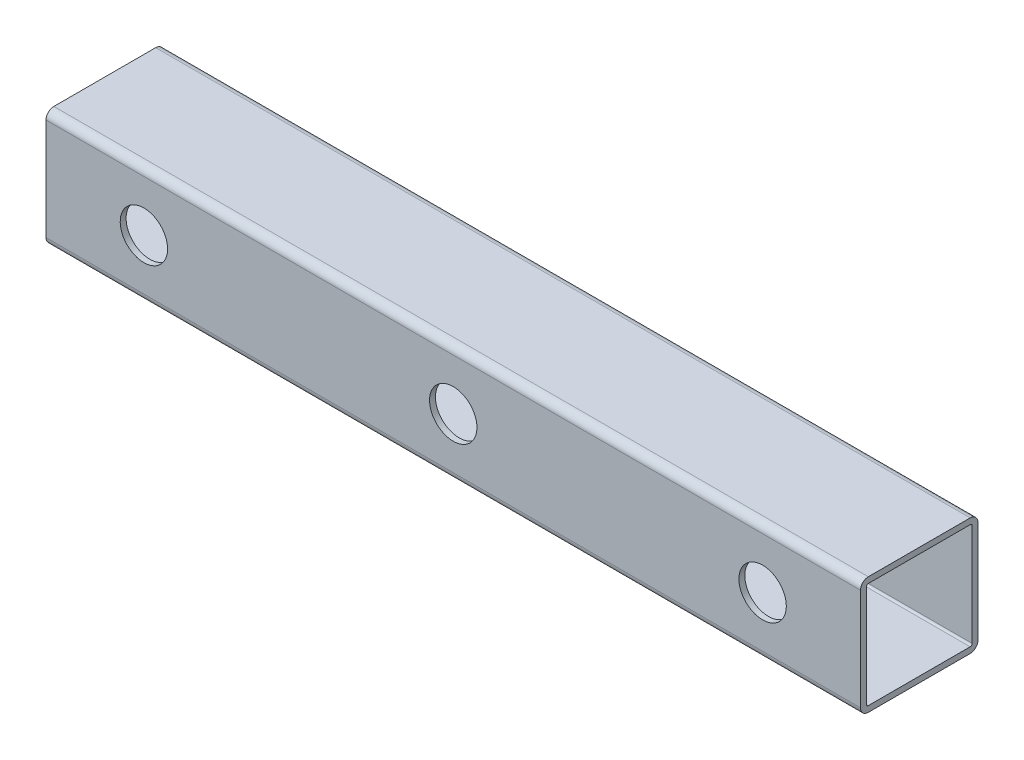
SolidWorks part; units mm, degrees
material "AISI 304"
ref_plane "Спереди" through (0, 0, 0) normal (0, 0, 1) x (1, 0, 0)
ref_plane "Сверху" through (0, 0, 0) normal (0, 1, 0) x (1, 0, 0)
ref_plane "Справа" through (0, 0, 0) normal (1, 0, 0) x (0, 0, -1)
other "Configuration Table"
sketch "Эскиз1" plane through (0, 0, 0) normal (1, 0, 0) x (0, 0, -1)
  line L0 (-26, 27) -> (26, 27)
  line L1 (-26, -30) -> (26, -30)
  line L2 (-30, -26) -> (-30, 26)
  line L3 (-26, 30) -> (26, 30)
  line L4 (30, -26) -> (30, 26)
  line L5 (-30, -30) -> (30, 30) construction
  line L6 (-30, 30) -> (30, -30) construction
  line L7 (27, -26) -> (27, 26)
  line L8 (-26, -27) -> (26, -27)
  line L9 (-27, -26) -> (-27, 26)
  arc A0 (-26, -30) -> (-30, -26) centre (-26, -26) cw
  arc A1 (26, -30) -> (30, -26) centre (26, -26) ccw
  arc A2 (26, 30) -> (30, 26) centre (26, 26) cw
  arc A3 (-30, 26) -> (-26, 30) centre (-26, 26) cw
  arc A4 (26, 27) -> (27, 26) centre (26, 26) cw
  arc A5 (26, -27) -> (27, -26) centre (26, -26) ccw
  arc A6 (-26, -27) -> (-27, -26) centre (-26, -26) cw
  arc A7 (-27, 26) -> (-26, 27) centre (-26, 26) cw
  point P0 (0, 0)
  dimension "D3" = 4
  dimension "D5" = 1
  dimension "D1" = 60
  dimension "D2" = 60
  dimension "D4" = 3
extrude "Бобышка-Вытянуть1" add sketch "Эскиз1" along normal mid plane 416
sketch "Эскиз3" plane through (0, -30, 0) normal (0, -1, 0) x (1, 0, 0)
  line L0 (0, -1) -> (0, 0) construction
  line L1 (-4, -16) -> (4, -16)
  line L2 (-4, -16) -> (-4, 14)
  line L3 (-4, 14) -> (4, 14)
  line L4 (4, -16) -> (4, 14)
  line L5 (-4, -16) -> (4, 14) construction
  line L6 (-4, 14) -> (4, -16) construction
  point P0 (0, -1)
  dimension "D1" = 8
  dimension "D2" = 30
  dimension "D3" = 1
extrude "Вырез-Вытянуть1" [suppressed] cut sketch "Эскиз3" against normal up to surface (3 mm away)
pattern_linear "Линейный массив1" [suppressed] count 13 spacing 24 count 13 spacing 24
sketch "Эскиз5" plane through (0, -30, 0) normal (0, -1, 0) x (1, 0, 0)
  line L0 (0, 0) -> (0, 59.1078) construction
  line L1 (-183, -10) -> (-183, 10) construction
  line L4 (-193.25, -10) -> (-193.25, 10) construction
  line L8 (-193.25, -20.25) -> (-172.75, -20.25)
  line L9 (-193.25, -20.25) -> (-193.25, 20.25)
  line L10 (-172.75, -10) -> (-172.75, 10) construction
  line L11 (183, -10) -> (183, 10) construction
  line L12 (193.25, -10) -> (193.25, 10) construction
  line L13 (172.75, -10) -> (172.75, 10) construction
  line L14 (-208, 26) -> (-208, -26) construction
  line L15 (-183, 0) -> (183, 0) construction
  line L16 (-193.25, 20.25) -> (-172.75, 20.25)
  line L17 (-172.75, -20.25) -> (-172.75, 20.25)
  line L18 (-193.25, -20.25) -> (-172.75, 20.25) construction
  line L19 (-193.25, 20.25) -> (-172.75, -20.25) construction
  line L20 (172.75, -20.25) -> (193.25, -20.25)
  line L21 (172.75, -20.25) -> (172.75, 20.25)
  line L22 (172.75, 20.25) -> (193.25, 20.25)
  line L23 (193.25, -20.25) -> (193.25, 20.25)
  line L24 (172.75, -20.25) -> (193.25, 20.25) construction
  line L25 (172.75, 20.25) -> (193.25, -20.25) construction
  arc A4 (-193.25, -10) -> (-172.75, -10) centre (-183, -10) ccw construction
  arc A5 (-172.75, 10) -> (-193.25, 10) centre (-183, 10) ccw construction
  arc A6 (193.25, -10) -> (172.75, -10) centre (183, -10) cw construction
  arc A7 (172.75, 10) -> (193.25, 10) centre (183, 10) cw construction
  point P5 (-183, 0)
  point P13 (183, 0)
  dimension "D3" = 40.5
  dimension "D1" = 20.5
  dimension "D2" = 25
  dimension "D4" = 20.5
  dimension "D5" = 40.5
extrude "Вырез-Вытянуть2" [suppressed] cut sketch "Эскиз5" against normal up to surface (60 mm away)
sketch "Эскиз6" plane through (0, -30, 0) normal (0, -1, 0) x (1, 0, 0)
  line L0 (208, 26) -> (208, -26) construction
  line L1 (-152, -122.9818) -> (152, -122.9818)
  line L2 (-152, -122.9818) -> (-152, 122.9818)
  line L3 (-152, 122.9818) -> (152, 122.9818)
  line L4 (152, -122.9818) -> (152, 122.9818)
  line L5 (-152, -122.9818) -> (152, 122.9818) construction
  line L6 (-152, 122.9818) -> (152, -122.9818) construction
  point P0 (0, 0)
  dimension "D1" = 56
split line "Разделяющая линия1"
sketch "Эскиз10" plane through (0, 0, -30) normal (0, 0, -1) x (-1, 0, 0)
  line L0 (0, 0) -> (0, 67.7802) construction
  line L1 (-208, -26) -> (-208, 26) construction
  line L8 (-208, -17) -> (208, -17) construction
  line L9 (208, -26) -> (208, 26) construction
  line L10 (-152, -30) -> (152, -30) construction
  line L11 (-158, 0) -> (0, 0) construction
  circle A0 centre (-158, 0) radius 12.1
  circle A1 centre (158, 0) radius 12.1
  circle A2 centre (0, 0) radius 12.1
  dimension "D1" = 50
  dimension "D2" = 24.2
  dimension "D3" = 30
  dimension "D4" = 13
extrude "Вырез-Вытянуть5" cut sketch "Эскиз10" against normal up to surface (60 mm away) up to face at (0, 0, 30)
